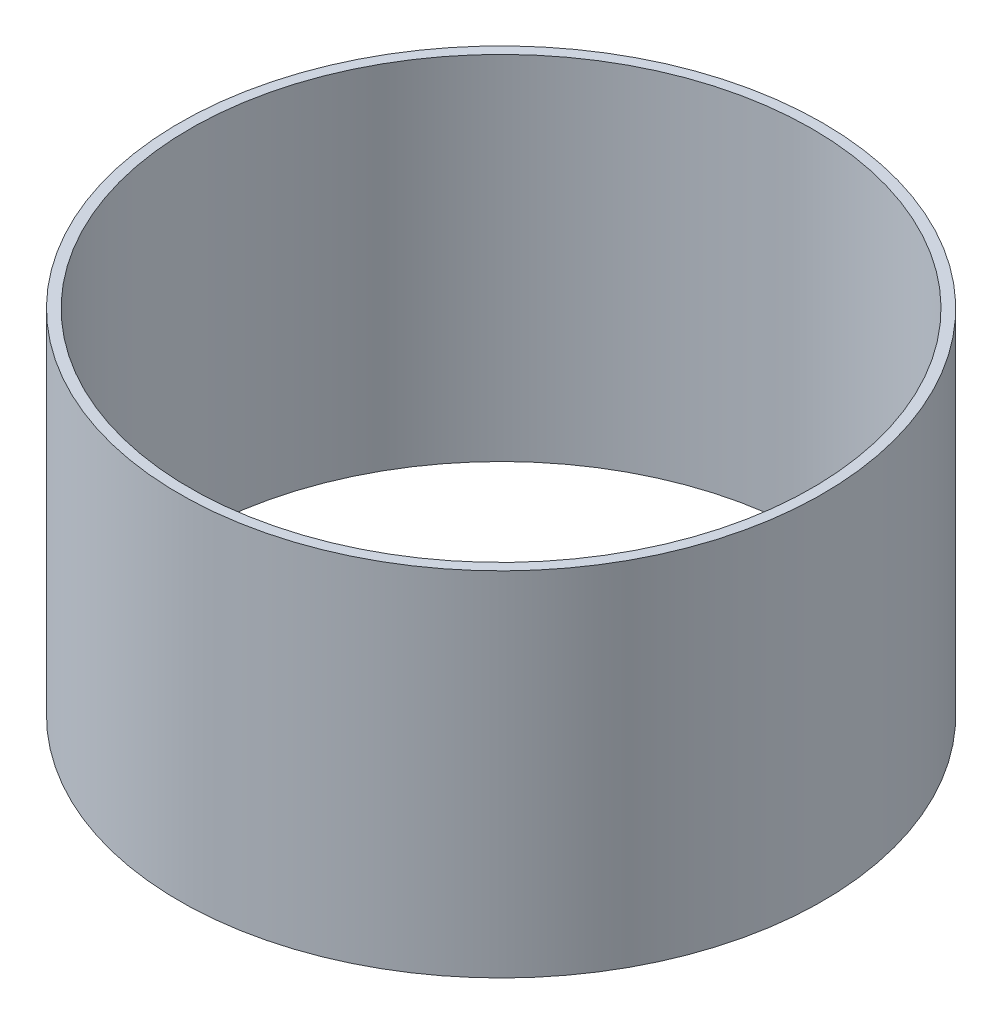
SolidWorks part; units mm, degrees
ref_plane "前视基准面" through (0, 0, 0) normal (0, 0, 1) x (1, 0, 0)
ref_plane "上视基准面" through (0, 0, 0) normal (0, 1, 0) x (1, 0, 0)
ref_plane "右视基准面" through (0, 0, 0) normal (1, 0, 0) x (0, 0, -1)
other "Configuration Table"
sketch "草图1" plane through (0, 0, 0) normal (0, 0, 1) x (1, 0, 0)
  line L0 (0, 0) -> (155, 0) construction
  line L5 (0, 0) -> (0, 18.9798) construction
  line L6 (155, 0) -> (150, 0)
  line L7 (155, 0) -> (155, 170)
  line L8 (155, 170) -> (150, 170)
  line L9 (150, 0) -> (150, 170)
  dimension "D1" = 170
  dimension "D2" = 150
  dimension "D3" = 155
revolve "旋转1" add sketch "草图1" angle 360 about L5
